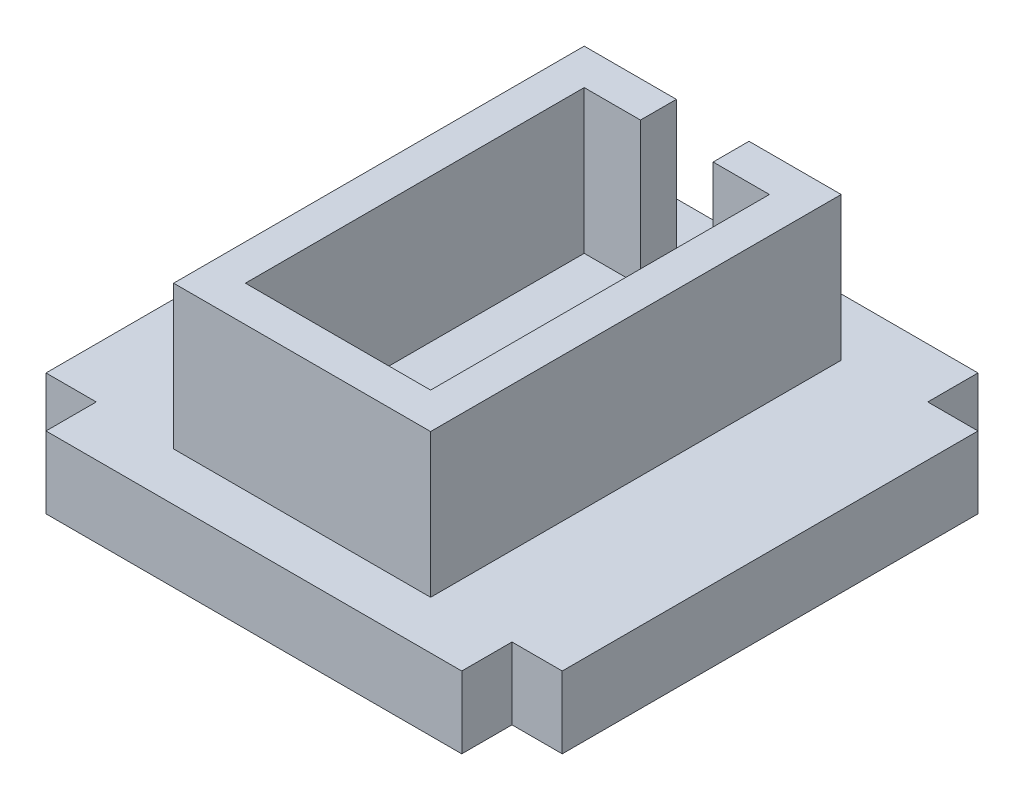
SolidWorks part; units mm, degrees
ref_plane "Front Plane" through (0, 0, 0) normal (0, 0, 1) x (1, 0, 0)
ref_plane "Top Plane" through (0, 0, 0) normal (0, 1, 0) x (1, 0, 0)
ref_plane "Right Plane" through (0, 0, 0) normal (1, 0, 0) x (0, 0, -1)
sketch "Sketch21" plane through (0, 0, 0) normal (0, 1, 0) x (1, 0, 0)
  line L22 (0, 17.98) -> (-14.48, 17.98)
  line L23 (-14.48, 17.98) -> (-14.48, 14.48)
  line L24 (-14.48, 14.48) -> (-17.98, 14.48)
  line L25 (-17.98, -14.48) -> (-14.48, -14.48)
  line L26 (-14.48, -14.48) -> (-14.48, -17.98)
  line L27 (-14.48, -17.98) -> (0, -17.98)
  line L28 (0, -17.98) -> (14.48, -17.98)
  line L29 (14.48, -17.98) -> (14.48, -14.48)
  line L30 (14.48, -14.48) -> (17.98, -14.48)
  line L31 (17.98, 14.48) -> (14.48, 14.48)
  line L32 (14.48, 14.48) -> (14.48, 17.98)
  line L33 (14.48, 17.98) -> (0, 17.98)
  line L34 (-17.98, 0) -> (-17.98, 14.48)
  line L35 (-17.98, -14.48) -> (-17.98, 0)
  line L36 (17.98, 0) -> (17.98, 14.48)
  line L37 (17.98, 0) -> (17.98, -14.48)
  dimension "D1" = 3.5
  dimension "D2" = 14.48
  dimension "D3" = 14.48
  dimension "D4" = 35.96
  dimension "D5" = 35.96
  dimension "D13" = 14.48
extrude "Boss-Extrude18" add sketch "Sketch21" along normal blind 5
sketch "Sketch23" plane through (0, 5, 0) normal (0, 1, 0) x (1, 0, 0)
  line L0 (-8.95, 13.98) -> (-2.53, 13.98)
  line L2 (-8.95, 13.98) -> (-8.95, -14.62)
  line L3 (-8.95, -14.62) -> (8.95, -14.62)
  line L4 (8.95, 13.98) -> (8.95, -14.62)
  line L5 (-2.53, 13.98) -> (-2.53, 11.48)
  line L6 (-2.53, 11.48) -> (-6.45, 11.48)
  line L7 (-6.45, 11.48) -> (-6.45, -12.12)
  line L8 (-6.45, -12.12) -> (6.45, -12.12)
  line L9 (6.45, -12.12) -> (6.45, 11.48)
  line L10 (6.45, 11.48) -> (2.53, 11.48)
  line L11 (2.53, 11.48) -> (2.53, 13.98)
  line L12 (2.53, 13.98) -> (8.95, 13.98)
  line L13 (14.48, 17.98) -> (-14.48, 17.98) construction
  point P0 (0, 0)
  dimension "D1" = 6.45
  dimension "D2" = 12.9
  dimension "D3" = 4
  dimension "D4" = 23.6
  dimension "D5" = 2.5
  dimension "D6" = 2.5
  dimension "D7" = 2.5
  dimension "D8" = 2.5
  dimension "D9" = 3.92
  dimension "D10" = 3.92
extrude "Boss-Extrude19" add sketch "Sketch23" along normal blind 10
